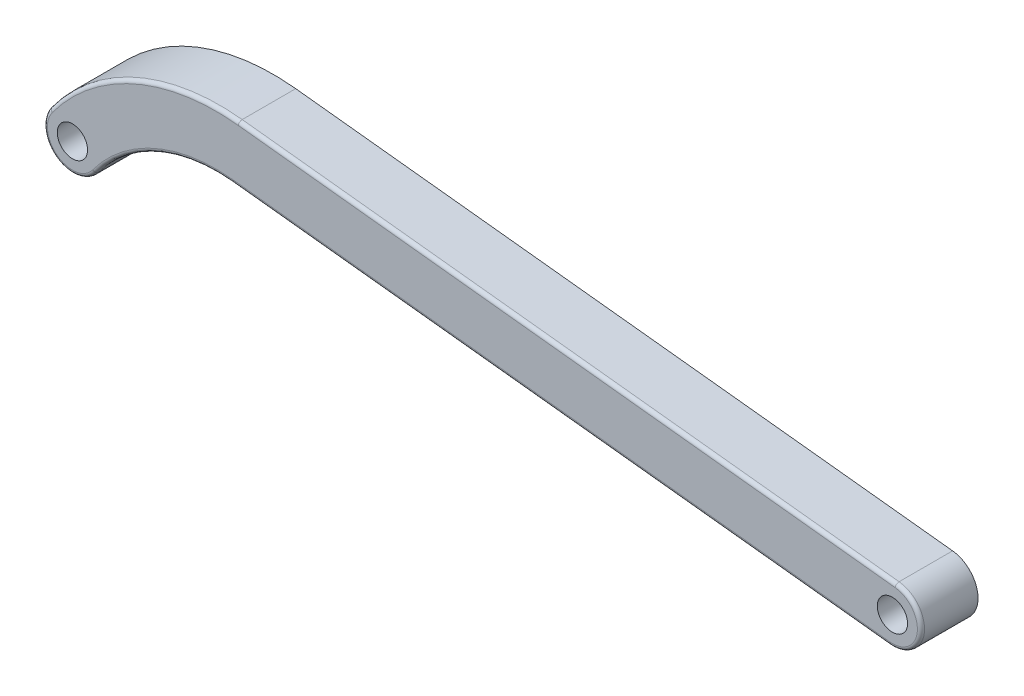
SolidWorks part; units mm, degrees
ref_plane "Front Plane" through (0, 0, 0) normal (0, 0, 1) x (1, 0, 0)
ref_plane "Top Plane" through (0, 0, 0) normal (0, 1, 0) x (1, 0, 0)
ref_plane "Right Plane" through (0, 0, 0) normal (1, 0, 0) x (0, 0, -1)
sketch "Sketch2" plane through (0, 0, 0) normal (0, 0, 1) x (1, 0, 0)
  line L0 (0, 0) -> (115, 0) construction
  line L1 (22.8811, 10.0726) -> (115, 0) construction
  line L2 (0, 0) -> (22.8811, 10.0726) construction
  line L3 (22.4463, 6.0963) -> (114.5652, -3.9763)
  line L4 (23.3158, 14.0489) -> (115.4348, 3.9763)
  arc A0 (0, 0) -> (22.8811, 10.0726) centre (20.1637, -14.7793) cw construction
  arc A1 (3.2262, -2.3647) -> (22.4463, 6.0963) centre (20.1637, -14.7793) cw
  arc A2 (-3.2262, 2.3647) -> (23.3158, 14.0489) centre (20.1637, -14.7793) cw
  arc A3 (-3.2262, 2.3647) -> (3.2262, -2.3647) centre (0, 0) ccw
  arc A4 (115.4348, 3.9763) -> (114.5652, -3.9763) centre (115, 0) cw
  circle A5 centre (0, 0) radius 2.125
  circle A6 centre (115, 0) radius 2.125
  dimension "D2" = 25
  dimension "D5" = 4.25
  dimension "D1" = 115
  dimension "D3" = 25
  dimension "D4" = 4
  dimension "D6" = 4
extrude "Boss-Extrude1" add sketch "Sketch2" along normal blind 8
fillet "Fillet2" radius 0.5 6 edges at (118.9763, -0.4348, 8) (69.3753, 9.0126, 8) (68.5057, 1.06, 8) (11.7027, 4.4408, 8) (-2.3647, -3.2262, 8) (8.4794, 11.7628, 8)
